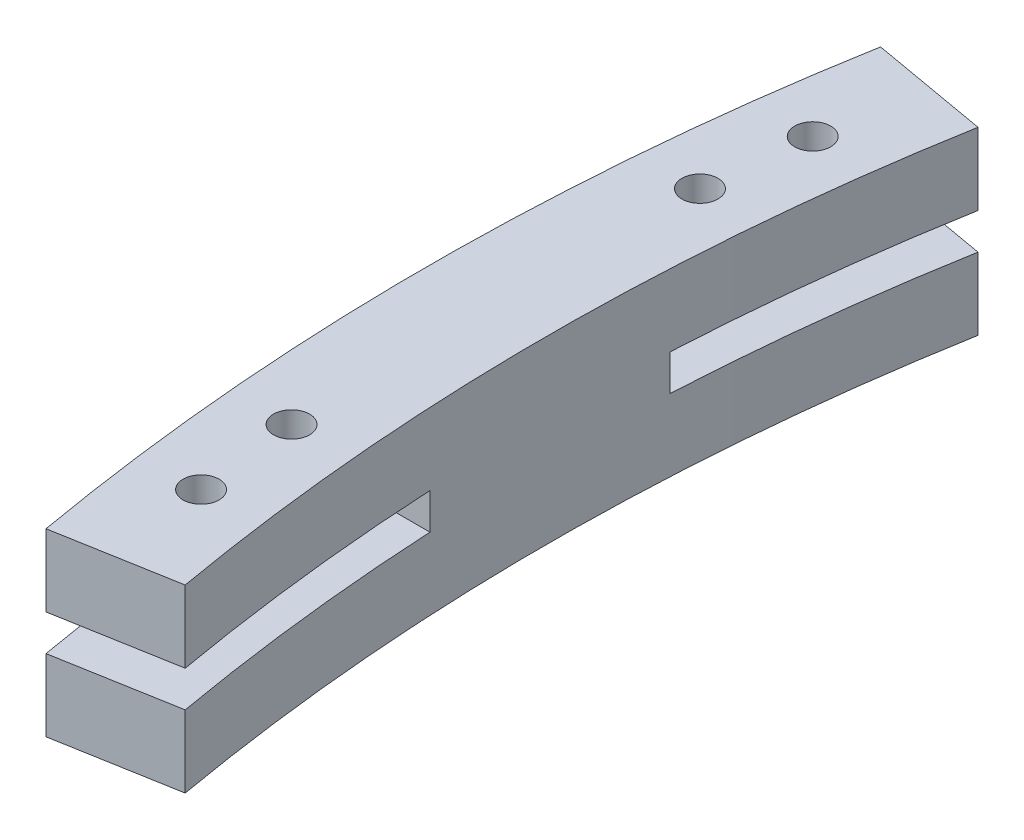
SolidWorks part; units mm, degrees
ref_plane "Front Plane" through (0, 0, 0) normal (0, 0, 1) x (1, 0, 0)
ref_plane "Top Plane" through (0, 0, 0) normal (0, 1, 0) x (1, 0, 0)
ref_plane "Right Plane" through (0, 0, 0) normal (1, 0, 0) x (0, 0, -1)
sketch "Sketch1" plane through (0, 0, 0) normal (0, 0, 1) x (1, 0, 0)
  line L0 (190, 0) -> (-190, 0) construction
  line L1 (0, 190) -> (0, -190) construction
  line L2 (0, 0) -> (-187.1135, 32.9932) construction
  line L3 (0, 0) -> (-187.1135, -32.9932) construction
  line L4 (-187.1135, 32.9932) -> (-196.9616, 34.7296)
  line L5 (-187.1135, -32.9932) -> (-196.9616, -34.7296)
  arc A0 (-187.1135, 32.9932) -> (-187.1135, -32.9932) centre (0, 0) ccw
  arc A1 (-196.9616, 34.7296) -> (-196.9616, -34.7296) centre (0, 0) ccw
  circle A3 centre (0, 0) radius 190 construction
  dimension "D1" = 380
  dimension "D2" = 10
  dimension "D3" = 20
sketch "Sketch9" plane through (0, 0, 0) normal (0, 1, 0) x (1, 0, 0)
  line L0 (0, 0) -> (-196.9616, 34.7296)
  line L1 (-200, 0) -> (200, 0) construction
  line L2 (0, 0) -> (-196.9616, -34.7296)
  circle A0 centre (0, 0) radius 195 construction
  circle A1 centre (0, 0) radius 195 construction
  circle A8 centre (0, 0) radius 200 construction
  circle A9 centre (0, 0) radius 190 construction
  circle A10 centre (0, 0) radius 200
  circle A11 centre (0, 0) radius 190
  dimension "D1" = 20
extrude "base" add sketch "Sketch9" along normal mid plane 15 contours A11 L0 A10 L2
sketch "Sketch11" plane through (0, 0, 0) normal (0, 1, 0) x (1, 0, 0)
  line L8 (-189.7367, -10) -> (-199.7498, -10) construction
  line L9 (-187.1135, -32.9932) -> (-196.9616, -34.7296) construction
  line L10 (-189.7367, 10) -> (-199.7498, 10) construction
  line L11 (-187.1135, 32.9932) -> (-196.9616, 34.7296) construction
  line L12 (-189.7367, -10) -> (-199.7498, -10)
  line L13 (-187.1135, -32.9932) -> (-196.9616, -34.7296)
  line L14 (-189.7367, 10) -> (-199.7498, 10)
  line L15 (-187.1135, 32.9932) -> (-196.9616, 34.7296)
  circle A14 centre (0, 0) radius 200 construction
  circle A15 centre (0, 0) radius 190 construction
  arc A16 (-196.9616, 34.7296) -> (-199.7498, 10) centre (0, 0) ccw
  arc A17 (-187.1135, 32.9932) -> (-189.7367, 10) centre (0, 0) ccw
  arc A18 (-199.7498, -10) -> (-196.9616, -34.7296) centre (0, 0) ccw
  arc A19 (-189.7367, -10) -> (-187.1135, -32.9932) centre (0, 0) ccw
extrude "mount" cut sketch "Sketch11" along normal up to surface and the other way up to surface
sketch "Sketch12" plane through (0, 0, 0) normal (0, 1, 0) x (1, 0, 0)
  line L0 (-200, 0) -> (200, 0) construction
  line L1 (-200, 0) -> (200, 0) construction
  line L2 (0, 0) -> (-193.3317, 25.4526) construction
  line L3 (0, 0) -> (-194.258, 16.9954) construction
  line L4 (0, 0) -> (-194.258, -16.9954) construction
  line L5 (0, 0) -> (-193.3317, -25.4526) construction
  circle A0 centre (0, 0) radius 195 construction
  circle A1 centre (0, 0) radius 195 construction
  circle A2 centre (-193.3317, 25.4526) radius 1.5
  circle A3 centre (-194.258, 16.9954) radius 1.5
  circle A4 centre (-194.258, -16.9954) radius 1.5
  circle A5 centre (-193.3317, -25.4526) radius 1.5
  dimension "D1" = 3
  dimension "D2" = 10
  dimension "D3" = 15
extrude "mount hole" cut sketch "Sketch12" against normal through all both and the other way through all
sketch "Sketch13" plane through (0, 0, 0) normal (0, 1, 0) x (1, 0, 0)
  line L0 (0, 0) -> (-195, 0) construction
  line L1 (-200, 0) -> (200, 0) construction
  line L3 (-193.75, 3) -> (-196.25, 3) construction
  line L4 (-193.75, 3) -> (-193.75, -3) construction
  line L5 (-193.75, -3) -> (-196.25, -3) construction
  line L6 (-196.25, 3) -> (-196.25, -3) construction
  line L7 (-193.75, 3) -> (-196.25, -3) construction
  line L8 (-193.75, -3) -> (-196.25, 3) construction
  line L13 (-196.25, 3) -> (-193.75, 3)
  line L14 (-196.25, 3) -> (-196.25, 0)
  line L15 (-196.25, 0) -> (-193.75, 0)
  line L16 (-193.75, 3) -> (-193.75, 0)
  circle A0 centre (0, 0) radius 195 construction
  dimension "D1" = 2.5
  dimension "D2" = 6
ref_plane "shaft" through (-195, 0, 0) normal (-1, 0, 0) x (0, 0, 1)
sketch "Sketch14" plane through (-195, 0, 0) normal (-1, 0, 0) x (0, 0, 1)
  circle A0 centre (0, 0) radius 1.5
  dimension "D1" = 3
extrude "shaft hole" cut sketch "Sketch14" along normal through all
revolve "bearing hole" cut sketch "Sketch13" angle 360 about L0
